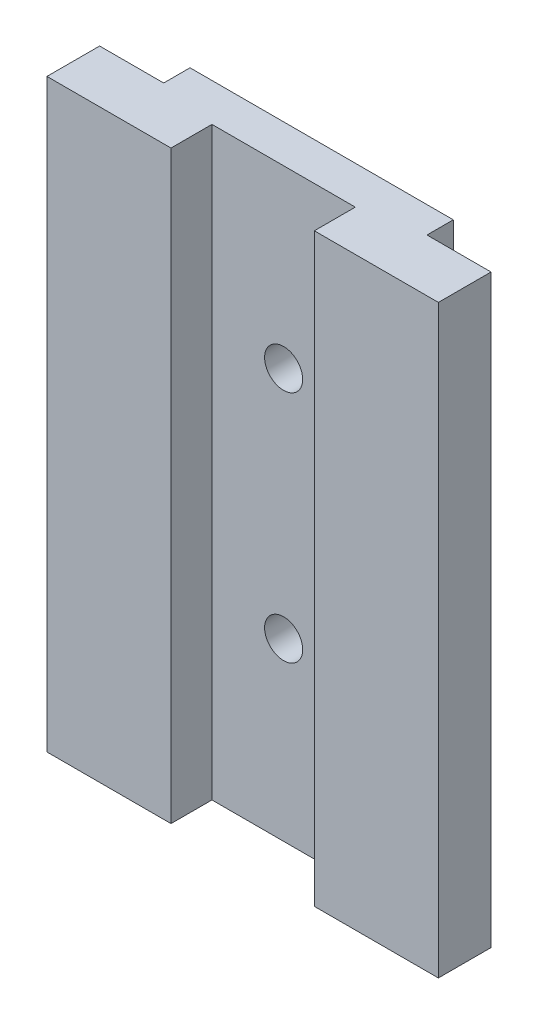
SolidWorks part; units mm, degrees
material "6061 Alloy"
ref_plane "Front Plane" through (0, 0, 0) normal (0, 0, 1) x (1, 0, 0)
ref_plane "Top Plane" through (0, 0, 0) normal (0, 1, 0) x (1, 0, 0)
ref_plane "Right Plane" through (0, 0, 0) normal (1, 0, 0) x (0, 0, -1)
sketch "Sketch1" plane through (0, 0, 0) normal (0, 1, 0) x (1, 0, 0)
  line L0 (0, 0) -> (11.43, 0)
  line L1 (0, 0) -> (-11.43, 0)
  line L2 (-11.43, 0) -> (-11.43, -2.286)
  line L3 (11.43, 0) -> (11.43, -2.286)
  line L4 (-11.43, -2.286) -> (-16.9926, -2.286)
  line L5 (11.43, -2.286) -> (16.9926, -2.286)
  line L6 (-16.9926, -2.286) -> (-16.9926, -6.858)
  line L7 (16.9926, -2.286) -> (16.9926, -6.858)
  line L8 (16.9926, -6.858) -> (6.223, -6.858)
  line L9 (-16.9926, -6.858) -> (-6.223, -6.858)
  line L10 (-6.223, -6.858) -> (-6.223, -3.302)
  line L11 (6.223, -6.858) -> (6.223, -3.302)
  line L12 (-6.223, -3.302) -> (6.223, -3.302)
  dimension "D1" = 11.43
  dimension "D2" = 11.43
  dimension "D3" = 2.286
  dimension "D4" = 2.286
  dimension "D5" = 5.5626
  dimension "D6" = 5.5626
  dimension "D7" = 4.572
  dimension "D8" = 4.572
  dimension "D9" = 10.7696
  dimension "D10" = 10.7696
  dimension "D11" = 3.556
  dimension "D12" = 3.556
extrude "Boss-Extrude1" add sketch "Sketch1" along normal blind 50.8
sketch "Sketch2" plane through (0, 0, 0) normal (0, 0, -1) x (-1, 0, 0)
  line L0 (-11.43, 0) -> (11.43, 0) construction
  circle A0 centre (0, 15.24) radius 2.921
  dimension "D2" = 5.842
  dimension "D1" = 15.24
extrude "Boss-Extrude2" add sketch "Sketch2" along normal blind 4.445
fillet "Fillet1" radius 0.254 1 edges at (-2.921, 15.24, -4.445)
sketch "Sketch3" plane through (0, 0, -4.445) normal (0, 0, -1) x (-1, 0, 0)
  circle A0 centre (0, 15.24) radius 1.651
  circle A1 centre (0, 15.24) radius 2.921 construction
  dimension "D2" = 1.27
  dimension "D1" = 15.24
extrude "Cut-Extrude1" cut sketch "Sketch3" against normal through all
sketch "Sketch4" plane through (0, 0, 0) normal (0, 0, -1) x (-1, 0, 0)
  line L0 (-11.43, 50.8) -> (11.43, 50.8) construction
  circle A0 centre (0, 35.56) radius 2.921
  dimension "D1" = 5.842
  dimension "D2" = 15.24
extrude "Boss-Extrude3" add sketch "Sketch4" along normal blind 4.445
fillet "Fillet2" radius 0.254 1 edges at (-2.921, 35.56, -4.445)
sketch "Sketch5" plane through (0, 0, -4.445) normal (0, 0, -1) x (-1, 0, 0)
  line L0 (-11.43, 50.8) -> (11.43, 50.8) construction
  circle A0 centre (0, 35.56) radius 1.651
  circle A1 centre (0, 35.56) radius 2.921 construction
  dimension "D2" = 1.27
  dimension "D1" = 15.24
extrude "Cut-Extrude2" cut sketch "Sketch5" against normal through all
